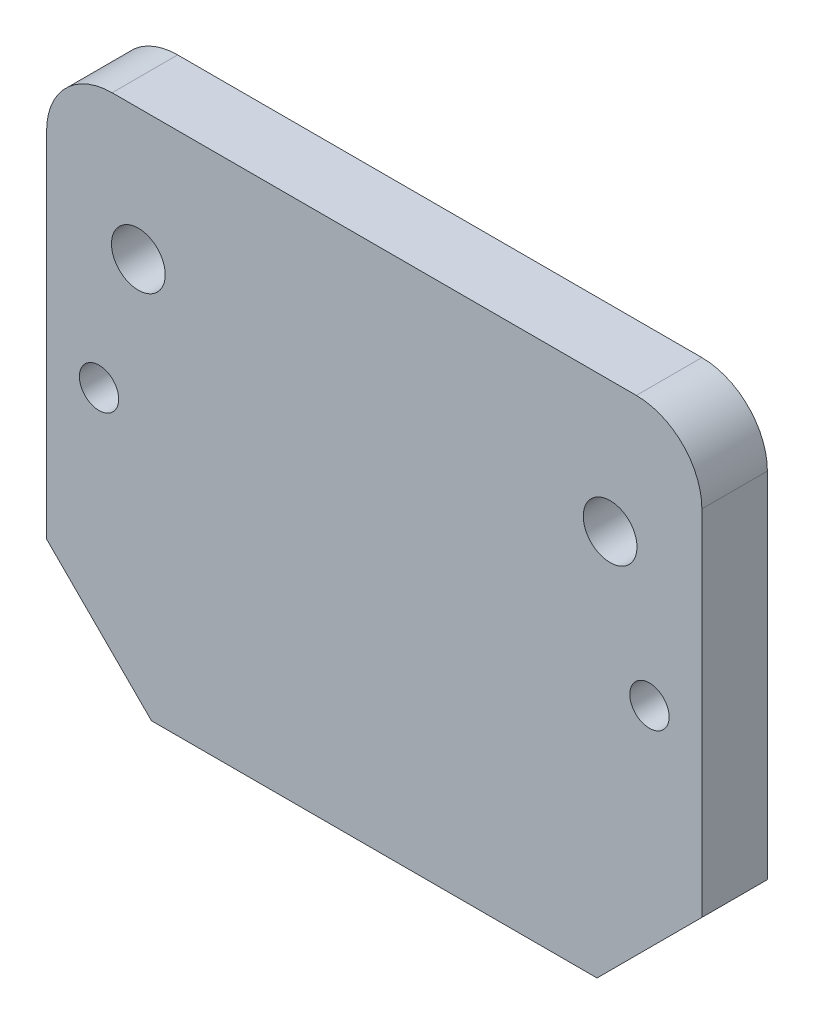
SolidWorks part; units mm, degrees
ref_plane "Plan de face" through (0, 0, 0) normal (0, 0, 1) x (1, 0, 0)
ref_plane "Plan de dessus" through (0, 0, 0) normal (0, 1, 0) x (1, 0, 0)
ref_plane "Plan de droite" through (0, 0, 0) normal (1, 0, 0) x (0, 0, -1)
sketch "Esquisse1" plane through (0, 0, 0) normal (0, 0, 1) x (1, 0, 0)
  line L0 (0, 0) -> (-8, 8)
  line L1 (-8, 8) -> (-8, 40)
  line L2 (-8, 40) -> (42, 40)
  line L3 (0, 31.2234) -> (0, 0) construction
  line L4 (0, 0) -> (34, 0)
  line L5 (17, 0) -> (17, 40) construction
  line L6 (-8, 8) -> (42, 8) construction
  line L7 (34, 31.2234) -> (34, 0) construction
  line L8 (42, 8) -> (42, 40)
  line L9 (34, 0) -> (42, 8)
  point P9 (17, 8)
  dimension "D1" = 50
  dimension "D2" = 40
  dimension "D3" = 135
  dimension "D4" = 8
extrude "Boss.-Extru.1" add sketch "Esquisse1" along normal blind 5
sketch "Esquisse3" plane through (0, 0, 0) normal (0, 0, -1) x (-1, 0, 0)
  line L0 (-17, 0) -> (-17, 40) construction
  line L1 (0, 0) -> (-34, 0) construction
  line L2 (-42, 40) -> (8, 40) construction
  circle A0 centre (4, 20) radius 1.5
  circle A1 centre (-38, 20) radius 1.5
  circle A2 centre (-35, 30) radius 2.05
  circle A3 centre (1, 30) radius 2.05
  dimension "D1" = 3
  dimension "D3" = 20
  dimension "D4" = 4.1
  dimension "D5" = 36
  dimension "D6" = 30
  dimension "D2" = 42
extrude "Enlèv. mat.-Extru.2" cut sketch "Esquisse3" against normal through all both and the other way through all
fillet "Congé1" radius 5 2 edges at (-8, 40, 2.5) (42, 40, 2.5)
